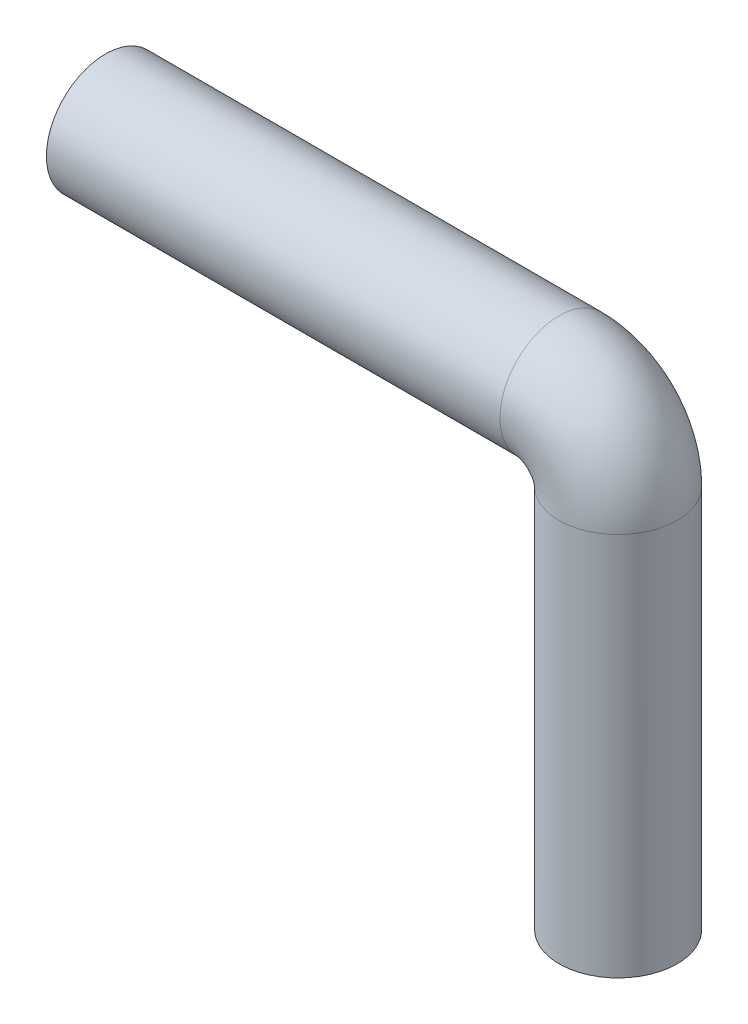
SolidWorks part; units mm, degrees
ref_plane "Front Plane" through (0, 0, 0) normal (0, 0, 1) x (1, 0, 0)
ref_plane "Top Plane" through (0, 0, 0) normal (0, 1, 0) x (1, 0, 0)
ref_plane "Right Plane" through (0, 0, 0) normal (1, 0, 0) x (0, 0, -1)
ref_plane "Plane1" through (0, 0, 0) normal (0, 0, -1) x (-1, 0, 0)
sketch "Sketch1" plane through (0, 0, 0) normal (0, 0, -1) x (-1, 0, 0)
  line L0 (-11.9728, -8.2333) -> (-11.9728, -7.9833)
  line L1 (-11.9728, -7.9833) -> (-0.9121, -7.9833)
  line L2 (-0.9121, -7.9833) -> (-0.9121, -6.5333)
  line L3 (-0.9121, -6.5333) -> (-1.9121, -6.5333)
  line L4 (-1.9121, -6.5333) -> (-1.9121, -6.7833)
  line L5 (-1.9121, -6.7833) -> (-12.9121, -6.7833)
  line L6 (-12.4728, -8.2333) -> (-11.9728, -8.2333)
  line L7 (-12.1757, -8.5333) -> (0.2029, -8.5333) construction
  arc A0 (-12.9121, -6.7833) -> (-12.4728, -8.2333) centre (-12.4728, -7.4417) ccw
  dimension "D1" = 11
  dimension "D2" = 4
  dimension "D3" = 0.25
  dimension "D4" = 0.25
  dimension "D5" = 1.45
  dimension "D6" = 1
  dimension "D7" = 0.5
revolve "Revolve1" add sketch "Sketch1" angle 360 about L7
sketch "Sketch5" plane through (1.9121, 0, 0) normal (1, 0, 0) x (0, 0, -1)
  circle A0 centre (0, -8.5333) radius 1.75
extrude "Boss-Extrude2" add sketch "Sketch5" against normal through all
sketch "Sketch6" plane through (1.9121, 0, 0) normal (1, 0, 0) x (0, 0, -1)
  circle A0 centre (0, -8.5333) radius 1.75
extrude "Boss-Extrude3" add sketch "Sketch6" along normal up to surface (11.3532 mm away)
sketch "Sketch7" plane through (13.2654, 0, 0) normal (1, 0, 0) x (0, 0, -1)
  circle A0 centre (0, -8.5333) radius 2
  dimension "D1" = 4
sketch "Sketch8" plane through (0, 0, 0) normal (0, 0, 1) x (1, 0, 0)
  line L0 (13.2654, -8.5333) -> (16.2654, -8.5333)
  line L1 (13.2654, -10.5333) -> (13.2654, -6.5333) construction
  line L2 (18.2654, -10.5333) -> (18.2654, -23.5333)
  arc A0 (18.2654, -10.5333) -> (16.2654, -8.5333) centre (16.2654, -10.5333) ccw
  point P7 (18.2654, -8.5333)
  dimension "D3" = 2
  dimension "D1" = 5
  dimension "D2" = 15
sweep "Sweep2" add profiles "Sketch7" path "Sketch8"
sketch "Sketch9" plane through (1.9121, 0, 0) normal (1, 0, 0) x (0, 0, -1)
  circle A0 centre (0, -8.5333) radius 2
extrude "Boss-Extrude4" add sketch "Sketch9" along normal up to next
sketch "Sketch10" plane through (0.9121, 0, 0) normal (-1, 0, 0) x (0, 0, 1)
  circle A0 centre (0, -8.5333) radius 2
extrude "Boss-Extrude5" add sketch "Sketch10" against normal up to surface (15.3532 mm away)
